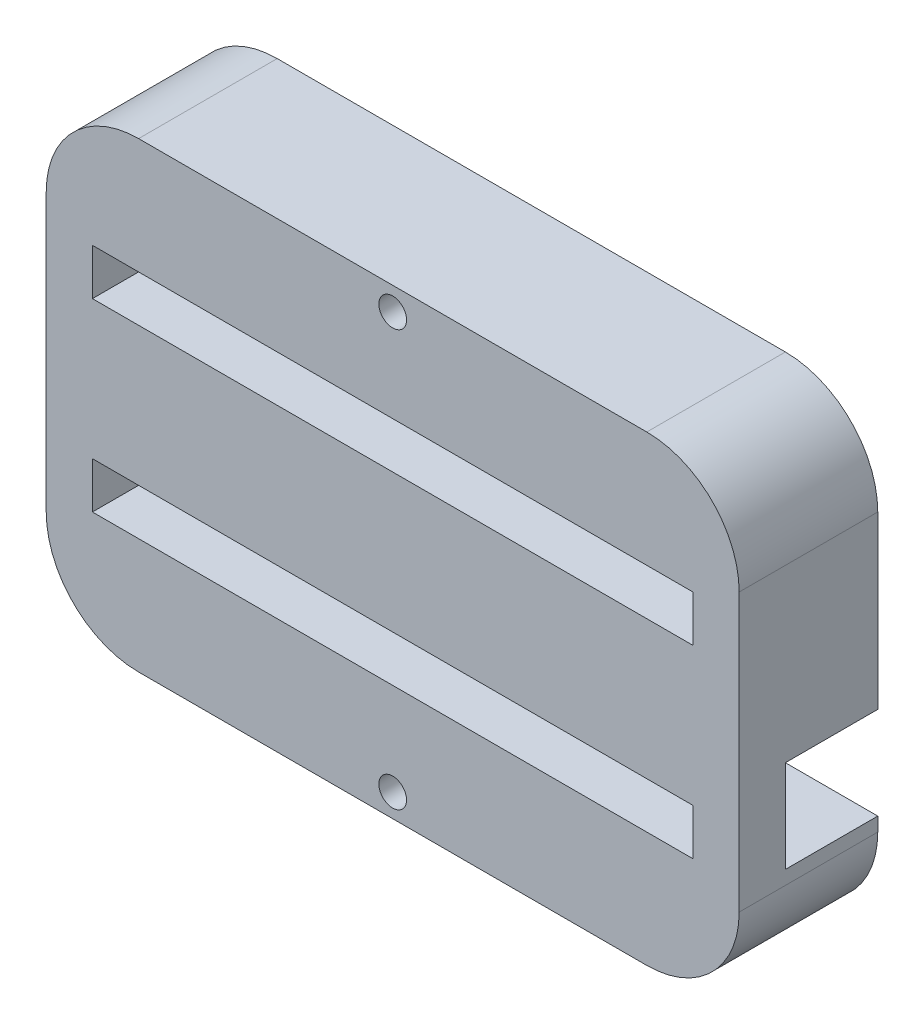
SolidWorks part; units mm, degrees
material "Custom Plastic"
ref_plane "Front Plane" through (0, 0, 0) normal (0, 0, 1) x (1, 0, 0)
ref_plane "Top Plane" through (0, 0, 0) normal (0, 1, 0) x (1, 0, 0)
ref_plane "Right Plane" through (0, 0, 0) normal (1, 0, 0) x (0, 0, -1)
sketch "Sketch1" plane through (0, 0, 0) normal (0, 0, 1) x (1, 0, 0)
  line L0 (2.9289, 47.0711) -> (23.1181, 32.5) construction
  line L1 (10, 0) -> (65, 0)
  line L2 (0, 10) -> (0, 40)
  line L3 (10, 50) -> (65, 50)
  line L4 (75, 10) -> (75, 40)
  line L5 (5, 37.5) -> (70, 37.5)
  line L6 (5, 37.5) -> (5, 32.5)
  line L7 (5, 32.5) -> (70, 32.5)
  line L8 (70, 37.5) -> (70, 32.5)
  line L9 (5, 17.5) -> (70, 17.5)
  line L10 (5, 17.5) -> (5, 12.5)
  line L11 (5, 12.5) -> (70, 12.5)
  line L12 (70, 17.5) -> (70, 12.5)
  line L13 (37.5, 50) -> (37.5, 0) construction
  line L14 (65, 0) -> (65, 12.5) construction
  line L15 (65, 50) -> (65, 37.5) construction
  arc A0 (65, 0) -> (75, 10) centre (65, 10) ccw
  arc A1 (0, 40) -> (10, 50) centre (10, 40) cw
  arc A2 (65, 50) -> (75, 40) centre (65, 40) cw
  arc A3 (10, 0) -> (0, 10) centre (10, 10) cw
  arc A9 (26.2495, 47.4653) -> (23.7505, 47.4653) centre (25, 25) ccw construction
  circle A10 centre (37.5, 47.5) radius 1.5
  circle A11 centre (37.5, 2.5) radius 1.5
  point P7 (75, 0)
  point P10 (0, 50)
  point P15 (0, 0)
  dimension "D3" = 10
  dimension "D12" = 3
  dimension "D13" = 3
  dimension "D1" = 50
  dimension "D2" = 75
  dimension "D4" = 5
  dimension "D5" = 5
  dimension "D6" = 15
  dimension "D8" = 5
  dimension "D9" = 5
  dimension "D10" = 5
  dimension "D11" = 70
  dimension "D14" = 2.5
  dimension "D15" = 2.5
extrude "Boss-Extrude1" add sketch "Sketch1" along normal blind 15
sketch "Sketch2" plane through (0, 0, 0) normal (-1, 0, 0) x (0, 0, 1)
  line L1 (0, 38.5) -> (10, 38.5)
  line L2 (0, 38.5) -> (0, 28.5)
  line L3 (0, 28.5) -> (10, 28.5)
  line L4 (10, 38.5) -> (10, 28.5)
  line L5 (0, 11.5) -> (10, 11.5)
  line L6 (0, 11.5) -> (0, 21.5)
  line L7 (0, 21.5) -> (10, 21.5)
  line L8 (10, 11.5) -> (10, 21.5)
  line L12 (0, 11.5) -> (0, 40) construction
  line L13 (10, 11.5) -> (10, 10) construction
  line L14 (15, 10) -> (0, 10) construction
  line L15 (10, 38.5) -> (10, 40) construction
  line L16 (15, 40) -> (0, 40) construction
  dimension "D1" = 10
  dimension "D2" = 10
  dimension "D3" = 10
  dimension "D4" = 10
  dimension "D5" = 7
extrude "Cut-Extrude1" cut sketch "Sketch2" against normal up to surface (75 mm away) up to face at (75, 25, 7.5)
sketch "Sketch3" plane through (0, 0, 0) normal (0, 0, -1) x (-1, 0, 0)
  line L0 (0, 32.5) -> (-75, 32.5) construction
  line L1 (-20, 32.5) -> (-55, 32.5)
  line L2 (-20, 32.5) -> (-20, 17.5)
  line L3 (-20, 17.5) -> (-55, 17.5)
  line L4 (-55, 32.5) -> (-55, 17.5)
  line L5 (-75, 17.5) -> (0, 17.5) construction
  line L6 (0, 32.5) -> (0, 17.5) construction
  line L7 (-75, 17.5) -> (-75, 32.5) construction
  dimension "D1" = 20
  dimension "D2" = 20
extrude "Cut-Extrude2" cut sketch "Sketch3" against normal up to surface (10 mm away) up to face at (37.5, 35, 10)
sketch "Sketch4" plane through (0, 0, 10) normal (0, 0, -1) x (-1, 0, 0)
  line L0 (-37.5, 32.5) -> (-37.5, 17.5) construction
  line L1 (-5, 32.5) -> (-70, 32.5) construction
  line L2 (-70, 17.5) -> (-5, 17.5) construction
  circle A0 centre (-37.5, 25) radius 1.7228
extrude "Cut-Extrude3" cut sketch "Sketch4" against normal blind 0.5
sketch "Sketch5" plane through (0, 0, 10) normal (0, 0, -1) x (-1, 0, 0)
  line L0 (-70, 32.5) -> (-70, 28.5)
  line L1 (-75, 28.5) -> (-55, 28.5) construction
  line L2 (-75, 11.5) -> (0, 11.5) construction
  line L3 (-70, 28.5) -> (-75, 28.5)
  line L4 (-70, 28.5) -> (-70, 38.5)
  line L5 (-70, 38.5) -> (-75, 38.5)
  line L6 (-75, 28.5) -> (-75, 38.5)
  line L7 (0, 21.5) -> (-5, 21.5)
  line L8 (0, 21.5) -> (0, 11.5)
  line L9 (0, 11.5) -> (-5, 11.5)
  line L10 (-5, 21.5) -> (-5, 11.5)
  dimension "D1" = 5
extrude "Boss-Extrude2" add sketch "Sketch5" along normal up to surface (10 mm away) contours L8 L7 L10 L9 | L4 L3 L6 L5 up to face at (10, 25, 0)
